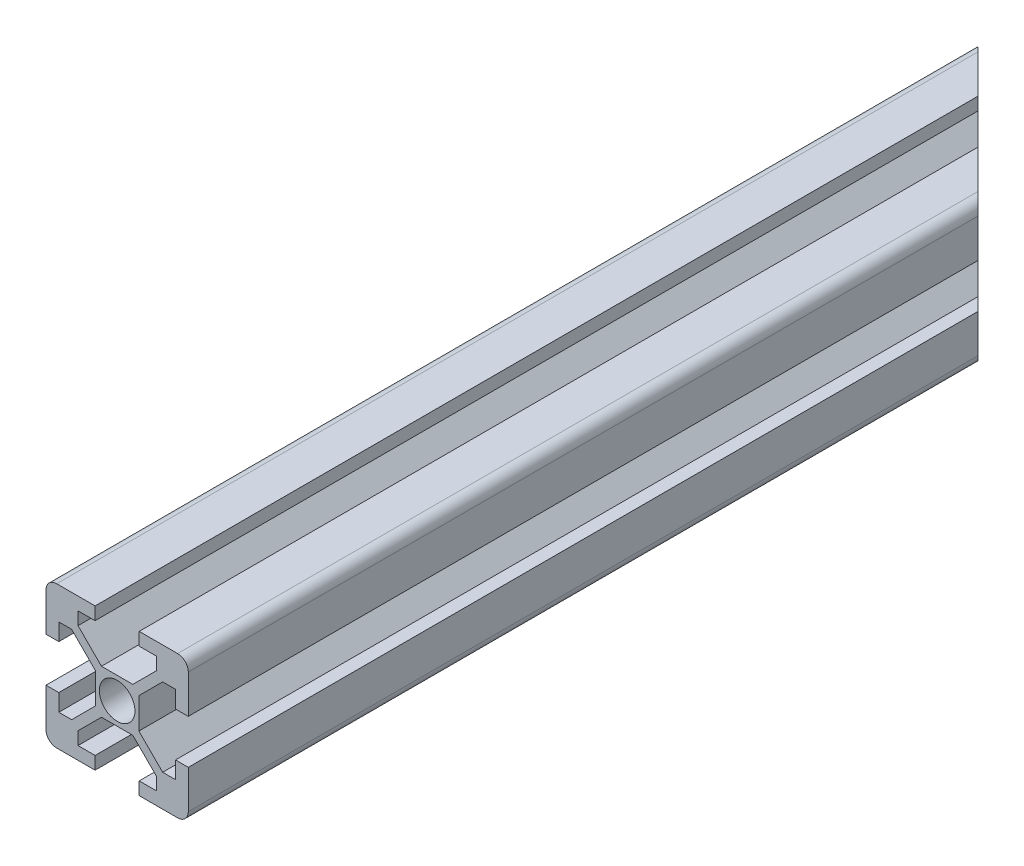
SolidWorks part; units mm, degrees
ref_plane "前视基准面" through (0, 0, 0) normal (0, 0, 1) x (1, 0, 0)
ref_plane "上视基准面" through (0, 0, 0) normal (0, 1, 0) x (1, 0, 0)
ref_plane "右视基准面" through (0, 0, 0) normal (1, 0, 0) x (0, 0, -1)
sketch "草图1" plane through (0, 0, 0) normal (0, 0, 1) x (1, 0, 0)
  line L0 (-10, -3.1) -> (-8.2, -3.1)
  line L1 (-8.5, 10) -> (8.5, 10)
  line L2 (-10, 8.5) -> (-10, -8.5)
  line L3 (-8.5, -10) -> (8.5, -10)
  line L4 (10, 8.5) -> (10, -8.5)
  line L5 (-10, 10) -> (10, -10) construction
  line L6 (-10, -10) -> (10, 10) construction
  line L7 (-3.0541, 3.1) -> (3.0541, 3.1)
  line L8 (-3.0541, 3.1) -> (-3.0541, -3.1)
  line L9 (-3.0541, -3.1) -> (3.0541, -3.1)
  line L10 (3.0541, 3.1) -> (3.0541, -3.1)
  line L11 (-3.0541, 3.1) -> (3.0541, -3.1) construction
  line L12 (-3.0541, -3.1) -> (3.0541, 3.1) construction
  line L13 (-8.2, -3.1) -> (-8.2, -5.5)
  line L14 (-8.2, -5.5) -> (-6.3971, -5.5)
  line L15 (-6.3971, -5.5) -> (-3.0541, -2.1571)
  line L16 (-5.5, 6.3971) -> (-2.1571, 3.0541)
  line L17 (-5.5, 8.2) -> (-5.5, 6.3971)
  line L18 (-3.1, 8.2) -> (-5.5, 8.2)
  line L19 (-3.1, 10) -> (-3.1, 8.2)
  line L20 (6.3971, 5.5) -> (3.0541, 2.1571)
  line L21 (8.2, 5.5) -> (6.3971, 5.5)
  line L22 (8.2, 3.1) -> (8.2, 5.5)
  line L23 (10, 3.1) -> (8.2, 3.1)
  line L24 (5.5, -6.3971) -> (2.1571, -3.0541)
  line L25 (5.5, -8.2) -> (5.5, -6.3971)
  line L26 (3.1, -8.2) -> (5.5, -8.2)
  line L27 (3.1, -10) -> (3.1, -8.2)
  line L28 (-3.1, -10) -> (-3.1, -8.2)
  line L29 (-3.1, -8.2) -> (-5.5, -8.2)
  line L30 (-5.5, -8.2) -> (-5.5, -6.3971)
  line L31 (-5.5, -6.3971) -> (-2.1571, -3.0541)
  line L32 (-8.2, 5.5) -> (-6.3971, 5.5)
  line L33 (-6.3971, 5.5) -> (-3.0541, 2.1571)
  line L34 (-8.2, 3.1) -> (-8.2, 5.5)
  line L35 (-10, 3.1) -> (-8.2, 3.1)
  line L36 (5.5, 8.2) -> (5.5, 6.3971)
  line L37 (5.5, 6.3971) -> (2.1571, 3.0541)
  line L38 (3.1, 8.2) -> (5.5, 8.2)
  line L39 (3.1, 10) -> (3.1, 8.2)
  line L40 (8.2, -5.5) -> (6.3971, -5.5)
  line L41 (6.3971, -5.5) -> (3.0541, -2.1571)
  line L42 (8.2, -3.1) -> (8.2, -5.5)
  line L43 (10, -3.1) -> (8.2, -3.1)
  circle A0 centre (0, 0) radius 2.5
  arc A1 (-10, 8.5) -> (-8.5, 10) centre (-8.5, 8.5) cw
  arc A2 (-10, -8.5) -> (-8.5, -10) centre (-8.5, -8.5) ccw
  arc A3 (8.5, 10) -> (10, 8.5) centre (8.5, 8.5) cw
  arc A4 (10, -8.5) -> (8.5, -10) centre (8.5, -8.5) cw
  point P0 (0, 0)
  point P20 (0, 0)
  point P26 (0, 0)
  point P32 (0, 0)
  point P38 (0, 0)
  point P60 (0, 0)
  dimension "D1" = 4
  dimension "D3" = 1.5
  dimension "D4" = 1.5
  dimension "D5" = 1.5
  dimension "D2" = 4
extrude "凸台-拉伸1" add sketch "草图1" along normal blind 371
sketch "草图2" plane through (0, 10, 0) normal (0, 1, 0) x (1, 0, 0)
  line L0 (10, 0) -> (10, -20)
  line L1 (10, -371) -> (10, 0) construction
  line L2 (10, -20) -> (-10, 0)
  line L3 (-10, 0) -> (10, 0)
extrude "切除-拉伸1" cut sketch "草图2" against normal through all
sketch "草图3" plane through (0, 0, 371) normal (0, 0, 1) x (1, 0, 0)
  line L1 (34.082, -32.429) -> (-14.9607, -32.429)
  line L2 (34.082, -32.429) -> (34.082, 13.3077)
  line L3 (34.082, 13.3077) -> (-14.9607, 13.3077)
  line L4 (-14.9607, -32.429) -> (-14.9607, 13.3077)
  line L5 (34.082, -32.429) -> (-14.9607, 13.3077) construction
  line L6 (34.082, 13.3077) -> (-14.9607, -32.429) construction
  arc A0 (8.5, -10) -> (10, -8.5) centre (8.5, -8.5) ccw construction
  point P0 (9.5607, -9.5607)
extrude "切除-拉伸2" cut sketch "草图3" against normal blind 240
